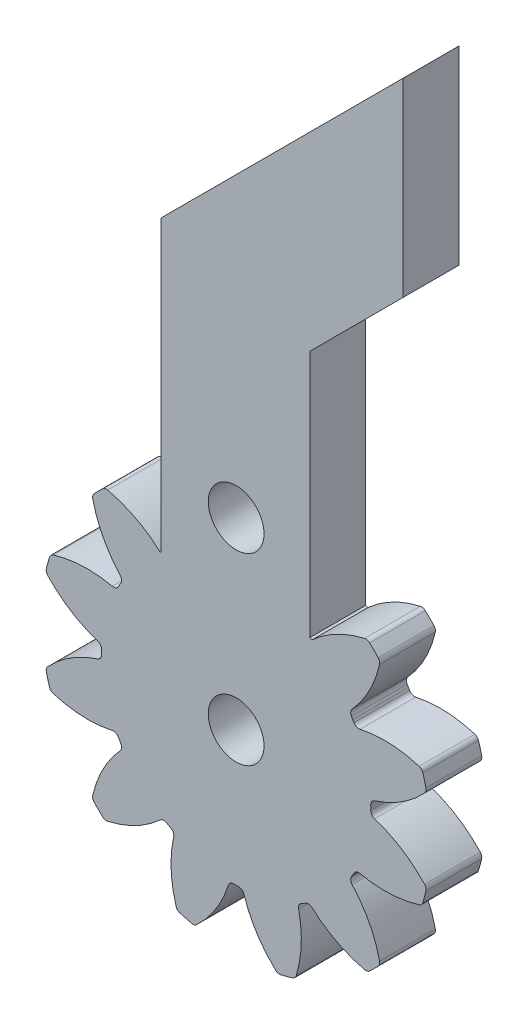
SolidWorks part; units mm, degrees
ref_plane "Plan de face" through (0, 0, 0) normal (0, 0, 1) x (1, 0, 0)
ref_plane "Plan de dessus" through (0, 0, 0) normal (0, 1, 0) x (1, 0, 0)
ref_plane "Plan de droite" through (0, 0, 0) normal (1, 0, 0) x (0, 0, -1)
sketch "Esquisse18" plane through (0, 0, 0) normal (0, 0, 1) x (1, 0, 0)
  line L0 (88.0303, -5.3051) -> (78.4084, 4.3168) construction
  line L1 (88.0303, -5.3051) -> (76.046, 1.614) construction
  line L2 (88.0303, -5.3051) -> (80.9003, 7.0445) construction
  line L3 (83.9953, 16.56) -> (97.0256, 29.5903)
  line L4 (83.9372, 0.9434) -> (83.9953, 0.9709)
  line L5 (83.9953, 16.56) -> (83.9953, 0.9709)
  line L6 (81.688, -1.7926) -> (81.7516, -1.6801)
  line L7 (91.9953, 14.3345) -> (91.9953, 0.9799)
  line L8 (97.0256, 29.5903) -> (97.0256, 19.3648)
  line L9 (97.0256, 19.3648) -> (91.9953, 14.3345)
  line L10 (92.1234, 0.9434) -> (91.9953, 0.9799)
  line L11 (80.7815, -5.4343) -> (80.7803, -5.3051)
  line L12 (81.8172, -9.0414) -> (81.7516, -8.9301)
  line L13 (84.4053, -11.5838) -> (84.5178, -11.6474)
  line L14 (88.0303, -12.5551) -> (88.1595, -12.5539)
  line L15 (91.6553, -11.5838) -> (91.7667, -11.5182)
  line L16 (94.309, -8.9301) -> (94.3726, -8.8176)
  line L17 (95.2803, -5.3051) -> (95.2792, -5.1759)
  line L18 (94.309, -1.6801) -> (94.2434, -1.5688)
  circle A0 centre (88.0303, -5.3051) radius 1.5
  circle A1 centre (88.0303, 4.5908) radius 1.5
  arc A2 (80.8391, 2.3458) -> (80.3794, 1.8861) centre (88.0303, -5.3051) ccw
  arc A3 (80.3054, 1.6141) -> (81.7818, -1.212) centre (86.4, 2.9993) ccw
  arc A4 (81.1111, 2.4198) -> (83.9372, 0.9434) centre (79.7259, -3.6748) cw
  arc A5 (81.8172, -1.5688) -> (81.7516, -1.6801) centre (88.0303, -5.3051) ccw
  arc A6 (80.3054, 1.6141) -> (80.3794, 1.8861) centre (80.598, 1.6806) cw
  arc A7 (81.1111, 2.4198) -> (80.8391, 2.3458) centre (81.0446, 2.1272) ccw
  arc A9 (81.7818, -1.212) -> (81.8172, -1.5688) centre (81.5601, -1.4141) cw
  arc A28 (94.9495, 2.4198) -> (92.1234, 0.9434) centre (96.3347, -3.6748) ccw
  arc A29 (94.9495, 2.4198) -> (95.2215, 2.3458) centre (95.016, 2.1272) cw
  arc A30 (95.6813, 1.8861) -> (95.2215, 2.3458) centre (88.0303, -5.3051) ccw
  arc A31 (95.7552, 1.6141) -> (95.6813, 1.8861) centre (95.4627, 1.6806) ccw
  arc A32 (95.7552, 1.6141) -> (94.2788, -1.212) centre (89.6606, 2.9993) cw
  arc A33 (94.2788, -1.212) -> (94.2434, -1.5688) centre (94.5005, -1.4141) ccw
  arc A34 (94.3726, -1.7926) -> (94.309, -1.6801) centre (88.0303, -5.3051) ccw
  arc A35 (94.6993, -1.9403) -> (94.3726, -1.7926) centre (94.6351, -1.6473) cw
  arc A36 (97.885, -2.0748) -> (94.6993, -1.9403) centre (96.0373, -8.0454) ccw
  arc A37 (97.885, -2.0748) -> (98.0835, -2.2748) centre (97.7963, -2.3614) cw
  arc A38 (98.2518, -2.9028) -> (98.0835, -2.2748) centre (88.0303, -5.3051) ccw
  arc A39 (98.1799, -3.1753) -> (98.2518, -2.9028) centre (97.9598, -2.9715) ccw
  arc A40 (98.1799, -3.1753) -> (95.4882, -4.8846) centre (93.5944, 1.0715) cw
  arc A41 (95.4882, -4.8846) -> (95.2792, -5.1759) centre (95.5791, -5.1705) ccw
  arc A42 (95.2792, -5.4343) -> (95.2803, -5.3051) centre (88.0303, -5.3051) ccw
  arc A43 (95.4882, -5.7256) -> (95.2792, -5.4343) centre (95.5791, -5.4397) cw
  arc A44 (98.1799, -7.4349) -> (95.4882, -5.7256) centre (93.5944, -11.6817) ccw
  arc A45 (98.1799, -7.4349) -> (98.2518, -7.7074) centre (97.9598, -7.6387) cw
  arc A46 (98.0835, -8.3354) -> (98.2518, -7.7074) centre (88.0303, -5.3051) ccw
  arc A47 (97.885, -8.5354) -> (98.0835, -8.3354) centre (97.7963, -8.2488) ccw
  arc A48 (97.885, -8.5354) -> (94.6993, -8.6699) centre (96.0373, -2.5648) cw
  arc A49 (94.6993, -8.6699) -> (94.3726, -8.8176) centre (94.6351, -8.9629) ccw
  arc A50 (94.2434, -9.0414) -> (94.309, -8.9301) centre (88.0303, -5.3051) ccw
  arc A51 (94.2788, -9.3982) -> (94.2434, -9.0414) centre (94.5005, -9.1961) cw
  arc A52 (95.7552, -12.2243) -> (94.2788, -9.3982) centre (89.6606, -13.6095) ccw
  arc A53 (95.7552, -12.2243) -> (95.6813, -12.4963) centre (95.4627, -12.2908) cw
  arc A54 (95.2215, -12.956) -> (95.6813, -12.4963) centre (88.0303, -5.3051) ccw
  arc A55 (94.9495, -13.03) -> (95.2215, -12.956) centre (95.016, -12.7374) ccw
  arc A56 (94.9495, -13.03) -> (92.1234, -11.5536) centre (96.3347, -6.9354) cw
  arc A57 (92.1234, -11.5536) -> (91.7667, -11.5182) centre (91.9213, -11.7753) ccw
  arc A58 (91.5428, -11.6474) -> (91.6553, -11.5838) centre (88.0303, -5.3051) ccw
  arc A59 (91.3951, -11.9741) -> (91.5428, -11.6474) centre (91.6882, -11.9098) cw
  arc A60 (91.2606, -15.1598) -> (91.3951, -11.9741) centre (85.29, -13.3121) ccw
  arc A61 (91.2606, -15.1598) -> (91.0606, -15.3583) centre (90.9741, -15.0711) cw
  arc A62 (90.4326, -15.5266) -> (91.0606, -15.3583) centre (88.0303, -5.3051) ccw
  arc A63 (90.1601, -15.4547) -> (90.4326, -15.5266) centre (90.3639, -15.2346) ccw
  arc A64 (90.1601, -15.4547) -> (88.4508, -12.763) centre (94.407, -10.8692) cw
  arc A65 (88.4508, -12.763) -> (88.1595, -12.5539) centre (88.1649, -12.8539) ccw
  arc A66 (87.9011, -12.5539) -> (88.0303, -12.5551) centre (88.0303, -5.3051) ccw
  arc A67 (87.6098, -12.763) -> (87.9011, -12.5539) centre (87.8957, -12.8539) cw
  arc A68 (85.9005, -15.4547) -> (87.6098, -12.763) centre (81.6537, -10.8692) ccw
  arc A69 (85.9005, -15.4547) -> (85.628, -15.5266) centre (85.6967, -15.2346) cw
  arc A70 (85, -15.3583) -> (85.628, -15.5266) centre (88.0303, -5.3051) ccw
  arc A71 (84.8, -15.1598) -> (85, -15.3583) centre (85.0866, -15.0711) ccw
  arc A72 (84.8, -15.1598) -> (84.6655, -11.9741) centre (90.7706, -13.3121) cw
  arc A73 (84.6655, -11.9741) -> (84.5178, -11.6474) centre (84.3725, -11.9098) ccw
  arc A74 (84.294, -11.5182) -> (84.4053, -11.5838) centre (88.0303, -5.3051) ccw
  arc A75 (83.9372, -11.5536) -> (84.294, -11.5182) centre (84.1394, -11.7753) cw
  arc A76 (81.1111, -13.03) -> (83.9372, -11.5536) centre (79.7259, -6.9354) ccw
  arc A77 (81.1111, -13.03) -> (80.8391, -12.956) centre (81.0446, -12.7374) cw
  arc A78 (80.3794, -12.4963) -> (80.8391, -12.956) centre (88.0303, -5.3051) ccw
  arc A79 (80.3054, -12.2243) -> (80.3794, -12.4963) centre (80.598, -12.2908) ccw
  arc A80 (80.3054, -12.2243) -> (81.7818, -9.3982) centre (86.4, -13.6095) cw
  arc A81 (81.7818, -9.3982) -> (81.8172, -9.0414) centre (81.5601, -9.1961) ccw
  arc A82 (81.688, -8.8176) -> (81.7516, -8.9301) centre (88.0303, -5.3051) ccw
  arc A83 (81.3613, -8.6699) -> (81.688, -8.8176) centre (81.4256, -8.9629) cw
  arc A84 (78.1756, -8.5354) -> (81.3613, -8.6699) centre (80.0234, -2.5648) ccw
  arc A85 (78.1756, -8.5354) -> (77.9771, -8.3354) centre (78.2643, -8.2488) cw
  arc A86 (77.8088, -7.7074) -> (77.9771, -8.3354) centre (88.0303, -5.3051) ccw
  arc A87 (77.8807, -7.4349) -> (77.8088, -7.7074) centre (78.1009, -7.6387) ccw
  arc A88 (77.8807, -7.4349) -> (80.5724, -5.7256) centre (82.4662, -11.6817) cw
  arc A89 (80.5724, -5.7256) -> (80.7815, -5.4343) centre (80.4815, -5.4397) ccw
  arc A90 (80.7815, -5.1759) -> (80.7803, -5.3051) centre (88.0303, -5.3051) ccw
  arc A91 (80.5724, -4.8846) -> (80.7815, -5.1759) centre (80.4815, -5.1705) cw
  arc A92 (77.8807, -3.1753) -> (80.5724, -4.8846) centre (82.4662, 1.0715) ccw
  arc A93 (77.8807, -3.1753) -> (77.8088, -2.9028) centre (78.1009, -2.9715) cw
  arc A94 (77.9771, -2.2748) -> (77.8088, -2.9028) centre (88.0303, -5.3051) ccw
  arc A95 (78.1756, -2.0748) -> (77.9771, -2.2748) centre (78.2643, -2.3614) ccw
  arc A96 (78.1756, -2.0748) -> (81.3613, -1.9403) centre (80.0234, -8.0454) cw
  arc A97 (81.3613, -1.9403) -> (81.688, -1.7926) centre (81.4256, -1.6473) ccw
  arc A98 (85.628, 4.9164) -> (85, 4.7481) centre (88.0303, -5.3051) ccw [skipped]
  arc A99 (84.8, 4.5496) -> (84.6655, 1.3639) centre (90.7706, 2.7019) ccw [skipped]
  arc A100 (85.9005, 4.8445) -> (87.6098, 2.1528) centre (81.6537, 0.259) cw [skipped]
  arc A101 (90.1601, 4.8445) -> (88.4508, 2.1528) centre (94.407, 0.259) ccw [skipped]
  arc A102 (88.4508, 2.1528) -> (88.1595, 1.9437) centre (88.1649, 2.2437) cw [skipped]
  arc A103 (88.1595, 1.9437) -> (88.0303, 1.9449) centre (88.0303, -5.3051) ccw [skipped]
  arc A105 (91.0606, 4.7481) -> (90.4326, 4.9164) centre (88.0303, -5.3051) ccw [skipped]
  arc A106 (90.1601, 4.8445) -> (90.4326, 4.9164) centre (90.3639, 4.6244) cw [skipped]
  arc A107 (91.2606, 4.5496) -> (91.3951, 1.3639) centre (85.29, 2.7019) cw [skipped]
  arc A108 (91.2606, 4.5496) -> (91.0606, 4.7481) centre (90.9741, 4.4609) ccw [skipped]
  arc A109 (85.9005, 4.8445) -> (85.628, 4.9164) centre (85.6967, 4.6244) ccw [skipped]
  arc A110 (84.8, 4.5496) -> (85, 4.7481) centre (85.0866, 4.4609) cw [skipped]
  arc A111 (91.7667, 0.908) -> (91.6553, 0.9736) centre (88.0303, -5.3051) ccw [skipped]
  arc A113 (84.5178, 1.0372) -> (84.4053, 0.9736) centre (88.0303, -5.3051) ccw [skipped]
  arc A114 (84.6655, 1.3639) -> (84.5178, 1.0372) centre (84.3725, 1.2996) cw [skipped]
  arc A115 (92.1234, 0.9434) -> (91.9953, 0.8743) centre (91.9213, 1.1651) cw [skipped]
  point P14 (80.2721, 1.7702)
  point P18 (80.955, 2.4532)
  point P21 (84.1015, 0.7881)
  point P24 (81.9371, -1.3763)
  point P192 (88.0303, -5.3051)
  dimension "D1" = 3
  dimension "D2" = 12.5
  dimension "D3" = 15
  dimension "D4" = 21
  dimension "D5" = 3
  dimension "D7" = 0.3
  dimension "D6" = 15
  dimension "D8" = 12
extrude "Boss.-Extru.18" add sketch "Esquisse18" along normal blind 3 separate body
